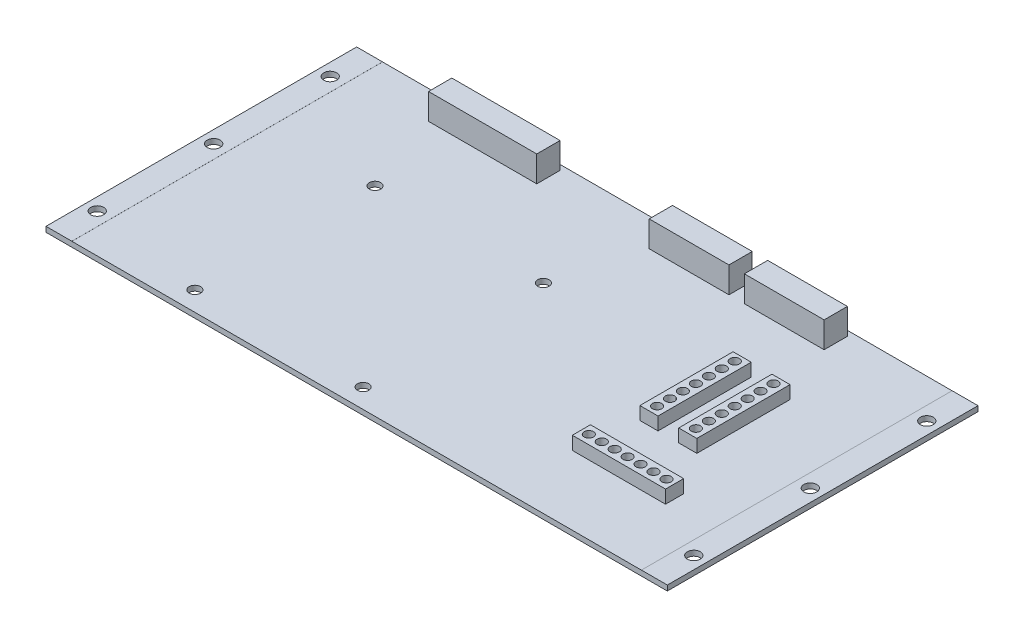
SolidWorks part; units mm, degrees
ref_plane "Front Plane" through (0, 0, 0) normal (0, 0, 1) x (1, 0, 0)
ref_plane "Top Plane" through (0, 0, 0) normal (0, 1, 0) x (1, 0, 0)
ref_plane "Right Plane" through (0, 0, 0) normal (1, 0, 0) x (0, 0, -1)
sketch "Sketch1" plane through (0, 0, 0) normal (0, 1, 0) x (1, 0, 0)
  line L0 (152.4, 152.4) -> (152.4, 0) construction
  line L1 (0, 0) -> (304.8, 0)
  line L2 (0, 0) -> (0, 152.4)
  line L3 (0, 152.4) -> (304.8, 152.4)
  line L4 (304.8, 0) -> (304.8, 152.4)
  line L5 (0, 76.2) -> (304.8, 76.2) construction
  circle A0 centre (298.7313, 76.2) radius 3.175
  circle A1 centre (298.7313, 133.35) radius 3.175
  circle A2 centre (298.7313, 19.05) radius 3.175
  circle A3 centre (6.0687, 19.05) radius 3.175
  circle A4 centre (6.0687, 76.2) radius 3.175
  circle A5 centre (6.0687, 133.35) radius 3.175
  circle A6 centre (63.5, 9.525) radius 2.794
  circle A7 centre (63.5, 97.917) radius 2.794
  circle A8 centre (146.05, 97.917) radius 2.794
  circle A9 centre (146.05, 9.525) radius 2.794
  dimension "D3" = 88.392
  dimension "D4" = 82.55
  dimension "D1" = 152.4
  dimension "D2" = 304.8
extrude "Board" add sketch "Sketch1" along normal blind 2.54
sketch "Sketch3" plane through (0, 2.54, 0) normal (0, 1, 0) x (-1, 0, 0)
  line L1 (-49.2246, -138.43) -> (-102.3106, -138.43)
  line L2 (-49.2246, -138.43) -> (-49.2246, -149.86)
  line L3 (-49.2246, -149.86) -> (-102.3106, -149.86)
  line L4 (-102.3106, -138.43) -> (-102.3106, -149.86)
  dimension "D1" = 53.086
  dimension "D2" = 11.43
extrude "D25toComputer" add sketch "Sketch3" along normal blind 12.7
sketch "Sketch5" plane through (0, 2.54, 0) normal (0, 1, 0) x (-1, 0, 0)
  line L1 (-157.4805, -138.43) -> (-196.5965, -138.43)
  line L2 (-157.4805, -138.43) -> (-157.4805, -149.86)
  line L3 (-157.4805, -149.86) -> (-196.5965, -149.86)
  line L4 (-196.5965, -138.43) -> (-196.5965, -149.86)
  line L6 (-204.1573, -138.43) -> (-243.2733, -138.43)
  line L7 (-204.1573, -138.43) -> (-204.1573, -149.86)
  line L8 (-204.1573, -149.86) -> (-243.2733, -149.86)
  line L9 (-243.2733, -138.43) -> (-243.2733, -149.86)
  dimension "D1" = 39.116
  dimension "D2" = 39.116
  dimension "D3" = 11.43
  dimension "D4" = 11.43
extrude "D15toMotor/Brake" add sketch "Sketch5" along normal blind 12.7
sketch "Sketch9" plane through (0, 2.54, 0) normal (0, 1, 0) x (-1, 0, 0)
  line L12 (-256.0807, -108.9227) -> (-256.0807, -63.2027)
  line L13 (-251.6357, -108.9227) -> (-251.6357, -63.2027) construction
  line L14 (-228.1407, -108.9227) -> (-237.0307, -108.9227)
  line L15 (-247.1907, -108.9227) -> (-256.0807, -108.9227)
  line L16 (-232.5857, -108.9227) -> (-232.5857, -63.2027) construction
  line L17 (-228.1407, -108.9227) -> (-228.1407, -63.2027)
  line L18 (-228.1407, -63.2027) -> (-237.0307, -63.2027)
  line L19 (-267.6607, -86.0627) -> (-276.5507, -86.0627) construction
  line L20 (-247.1907, -108.9227) -> (-247.1907, -63.2027)
  line L21 (-237.0307, -108.9227) -> (-237.0307, -63.2027)
  line L22 (-247.1907, -63.2027) -> (-256.0807, -63.2027)
  line L23 (-248.6107, -86.0627) -> (-257.5007, -86.0627) construction
  circle A14 centre (-251.6357, -73.5242) radius 2.286
  circle A15 centre (-232.5857, -79.8742) radius 2.286
  circle A16 centre (-232.5857, -67.1742) radius 2.286
  circle A17 centre (-251.6357, -67.1742) radius 2.286
  circle A18 centre (-251.6357, -86.2242) radius 2.286
  circle A19 centre (-251.6357, -79.8742) radius 2.286
  circle A20 centre (-251.6357, -98.9242) radius 2.286
  circle A21 centre (-232.5857, -98.9242) radius 2.286
  circle A22 centre (-232.5857, -105.2742) radius 2.286
  circle A23 centre (-251.6357, -92.5742) radius 2.286
  circle A24 centre (-251.6357, -105.2742) radius 2.286
  circle A25 centre (-232.5857, -73.5242) radius 2.286
  circle A26 centre (-232.5857, -86.2242) radius 2.286
  circle A27 centre (-232.5857, -92.5742) radius 2.286
extrude "Motors/Brakes" add sketch "Sketch9" along normal blind 6.35
sketch "Sketch10" plane through (0, 2.54, 0) normal (0, 1, 0) x (-1, 0, 0)
  line L0 (-304.8, -152.4) -> (0, -152.4) construction
  line L1 (-304.8, 0) -> (-292.1, 0)
  line L2 (-304.8, 0) -> (-304.8, -152.4)
  line L3 (-304.8, -152.4) -> (-292.1, -152.4)
  line L4 (-292.1, 0) -> (-292.1, -152.4)
  line L5 (-152.4, 0) -> (-152.4, -152.4) construction
  line L6 (0, 0) -> (-304.8, 0) construction
  line L7 (-304.8, -152.4) -> (0, -152.4) construction
  line L8 (-12.7, 0) -> (-12.7, -152.4)
  line L9 (0, -152.4) -> (-12.7, -152.4)
  line L10 (0, 0) -> (0, -152.4)
  line L11 (0, 0) -> (-12.7, 0)
  line L12 (-304.8, -76.2) -> (0, -76.2) construction
  circle A0 centre (-298.7313, -133.35) radius 3.175
  circle A1 centre (-298.7313, -76.2) radius 3.175
  circle A2 centre (-298.7313, -19.05) radius 3.175
  circle A3 centre (-6.0687, -19.05) radius 3.175
  circle A4 centre (-6.0687, -76.2) radius 3.175
  circle A5 centre (-6.0687, -133.35) radius 3.175
  dimension "D1" = 12.7
extrude "platedEdge" add sketch "Sketch10" along normal blind 0.0254
sketch "Sketch11" plane through (0, 2.54, 0) normal (0, 1, 0) x (-1, 0, 0)
  line L0 (-224.2846, -33.91) -> (-270.0046, -33.91)
  line L1 (-270.0046, -33.91) -> (-270.0046, -42.8)
  line L3 (-247.1446, -34.0326) -> (-247.1446, -42.9226) construction
  line L4 (-224.2846, -42.8) -> (-270.0046, -42.8)
  line L5 (-224.2846, -33.91) -> (-224.2846, -42.8)
  circle A0 centre (-259.6831, -38.355) radius 2.286
  circle A1 centre (-227.9331, -38.355) radius 2.286
  circle A2 centre (-253.3331, -38.355) radius 2.286
  circle A3 centre (-234.2831, -38.355) radius 2.286
  circle A4 centre (-246.9831, -38.355) radius 2.286
  circle A5 centre (-266.0331, -38.355) radius 2.286
  circle A6 centre (-240.6331, -38.355) radius 2.286
extrude "HVin/24Vin/5Vin" add sketch "Sketch11" along normal blind 6.4516
